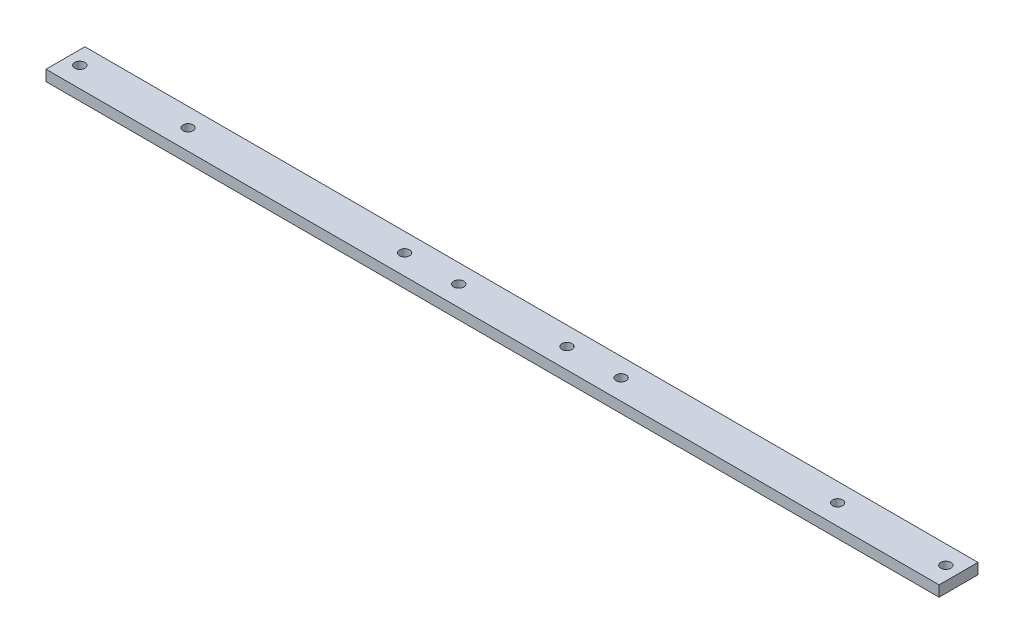
SolidWorks part; units mm, degrees
ref_plane "Front" through (0, 0, 0) normal (0, 0, 1) x (1, 0, 0)
ref_plane "Top" through (0, 0, 0) normal (0, 1, 0) x (1, 0, 0)
ref_plane "Right" through (0, 0, 0) normal (1, 0, 0) x (0, 0, -1)
sketch "Sketch1" plane through (0, 0, 0) normal (0, 1, 0) x (1, 0, 0)
  line L0 (0, 25.5356) -> (0, -1.4644)
  line L3 (0, 25.5356) -> (264, 25.5356)
  line L7 (0, -1.4644) -> (264, -1.4644)
  line L8 (264, -1.4644) -> (264, 25.5356)
  line L9 (264, -1.4644) -> (264, 10.5356)
  line L10 (264, 21.5356) -> (260, 21.5356)
  line L11 (0, 21.5356) -> (4, 21.5356)
  line L12 (4, 21.5356) -> (260, 21.5356)
  line L13 (4, 21.5356) -> (132, 21.5356)
  line L14 (132, 21.5356) -> (260, 21.5356)
  line L15 (264, 10.5356) -> (264, -1.4644)
  line L16 (264, 4.5356) -> (260, 4.5356)
  line L17 (132, 25.5356) -> (132, 23.5356)
  line L18 (4, 21.5356) -> (68, 21.5356)
  line L19 (68, 21.5356) -> (36, 21.5356)
  line L20 (36, 21.5356) -> (36, 4.5356)
  line L21 (196, 21.5356) -> (260, 21.5356)
  line L22 (228, 21.5356) -> (228, 4.5356)
  line L23 (132, 21.5356) -> (132, 4.5356)
  line L24 (132, 21.5356) -> (164, 21.5356)
  circle A0 centre (4, 21.5356) radius 2
  circle A1 centre (260, 21.5356) radius 2
  circle A2 centre (132, 21.5356) radius 2
  circle A3 centre (68, 21.5356) radius 2
  circle A4 centre (196, 21.5356) radius 2
  circle A5 centre (260, 4.5356) radius 1.5
  circle A6 centre (4, 4.5356) radius 1.5
  circle A7 centre (36, 4.5356) radius 1.5
  circle A8 centre (228, 4.5356) radius 1.5
  circle A9 centre (132, 4.5356) radius 1.5
  circle A10 centre (164, 21.5356) radius 2
  circle A11 centre (100, 21.5356) radius 2
  dimension "D5" = 23
  dimension "D6" = 128
  dimension "D9" = 4
  dimension "D10" = 32
  dimension "D1" = 4
  dimension "D2" = 264
  dimension "D3" = 4
  dimension "D4" = 4
  dimension "D7" = 128
  dimension "D8" = 12
extrude "Boss-Extrude1" add sketch "Sketch1" along normal blind 3.175
sketch "Sketch2" plane through (0, 3.175, 0) normal (0, 1, 0) x (1, 0, 0)
  line L0 (37.5, 4.5356) -> (228, 4.5356)
  line L1 (132, 21.5356) -> (132, 4.5356)
  line L2 (132, 4.5356) -> (148, 4.5356)
  line L3 (148, 4.5356) -> (116, 4.5356)
  line L4 (116, 4.5356) -> (100, 4.5356)
  line L5 (148, 4.5356) -> (164, 4.5356)
  circle A0 centre (36, 4.5356) radius 1.5 construction
  circle A1 centre (116, 4.5356) radius 1.5
  circle A2 centre (148, 4.5356) radius 1.5
  circle A3 centre (100, 4.5356) radius 1.5
  circle A4 centre (164, 4.5356) radius 1.5
  dimension "D3" = 16
  dimension "D1" = 16
  dimension "D2" = 16
  dimension "D4" = 16
extrude "Cut-Extrude1" cut sketch "Sketch2" against normal blind 10 contours A3 | A1 | A2 | A4
sketch "Sketch3" plane through (0, 3.175, 0) normal (0, 1, 0) x (1, 0, 0)
  line L0 (264, -1.4644) -> (264, 25.5356) construction
  line L1 (0, 25.5356) -> (264, 25.5356)
  line L2 (0, 25.5356) -> (0, 12.0356)
  line L3 (0, 12.0356) -> (264, 12.0356)
  line L4 (264, 25.5356) -> (264, 12.0356)
extrude "Cut-Extrude2" cut sketch "Sketch3" against normal blind 10
sketch "Sketch4" plane through (0, 3.175, 0) normal (0, 1, 0) x (1, 0, 0)
  line L0 (0, 12.0356) -> (264, 12.0356)
  line L1 (0, 12.0356) -> (0, 10.0356)
  line L2 (264, 12.0356) -> (264, 10.0356)
  line L3 (0, 10.0356) -> (264, 10.0356)
  line L4 (0, 12.0356) -> (264, 12.0356) construction
  dimension "D1" = 2
extrude "Cut-Extrude3" cut sketch "Sketch4" against normal blind 10
